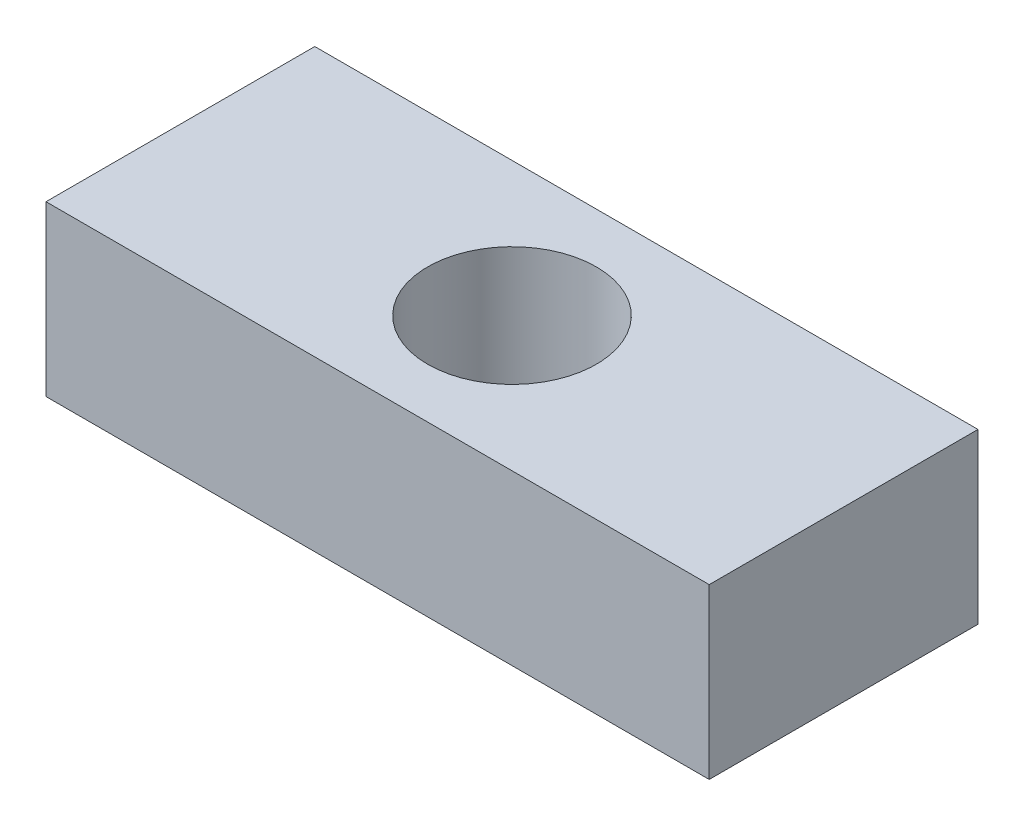
SolidWorks part; units mm, degrees
ref_plane "Front Plane" through (0, 0, 0) normal (0, 0, 1) x (1, 0, 0)
ref_plane "Top Plane" through (0, 0, 0) normal (0, 1, 0) x (1, 0, 0)
ref_plane "Right Plane" through (0, 0, 0) normal (1, 0, 0) x (0, 0, -1)
sketch "Sketch1" plane through (0, 0, 0) normal (0, 1, 0) x (1, 0, 0)
  line L1 (4.7414, -1.9216) -> (-4.7414, -1.9216)
  line L2 (4.7414, -1.9216) -> (4.7414, 1.9216)
  line L3 (4.7414, 1.9216) -> (-4.7414, 1.9216)
  line L4 (-4.7414, -1.9216) -> (-4.7414, 1.9216)
  line L5 (4.7414, -1.9216) -> (-4.7414, 1.9216) construction
  line L6 (4.7414, 1.9216) -> (-4.7414, -1.9216) construction
  circle A0 centre (0, 0) radius 1.2065
  point P0 (0, 0)
  dimension "D1" = 2.413
extrude "Boss-Extrude1" add sketch "Sketch1" along normal blind 2.413
